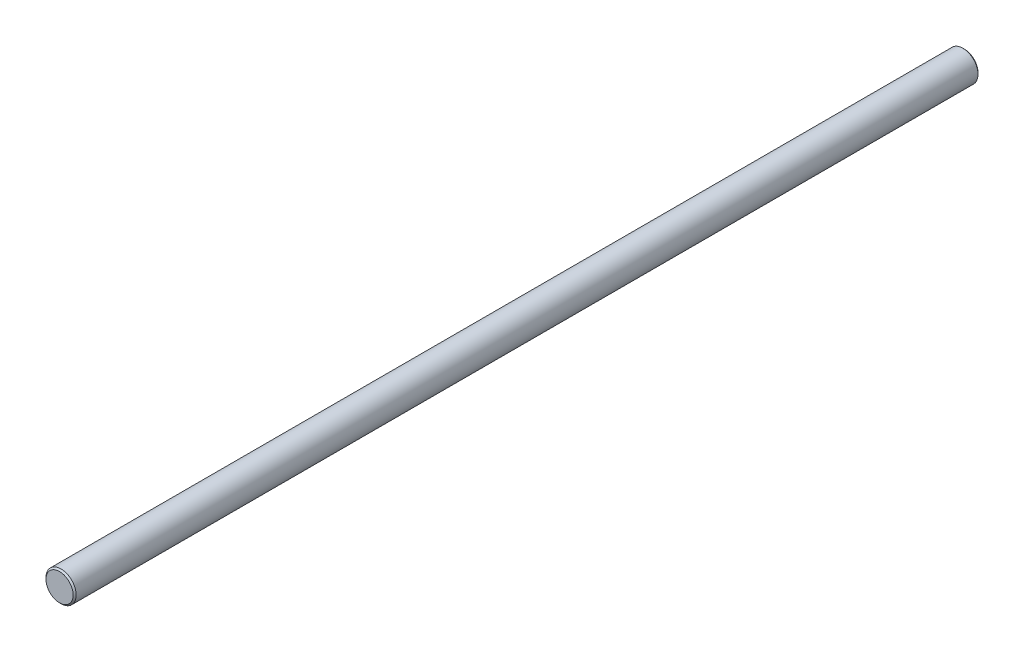
SolidWorks part; units mm, degrees
ref_plane "前视基准面" through (0, 0, 0) normal (0, 0, 1) x (1, 0, 0)
ref_plane "上视基准面" through (0, 0, 0) normal (0, 1, 0) x (1, 0, 0)
ref_plane "右视基准面" through (0, 0, 0) normal (1, 0, 0) x (0, 0, -1)
other "Configuration Table"
sketch "草图1" plane through (0, 0, 0) normal (0, 0, 1) x (1, 0, 0)
  circle A0 centre (0, 0) radius 5
  dimension "D1" = 10
extrude "凸台-拉伸1" add sketch "草图1" along normal blind 300
chamfer "倒角1" distance 0.5 angle 45 2 edges at (5, 0, 300) (5, 0, 0)
